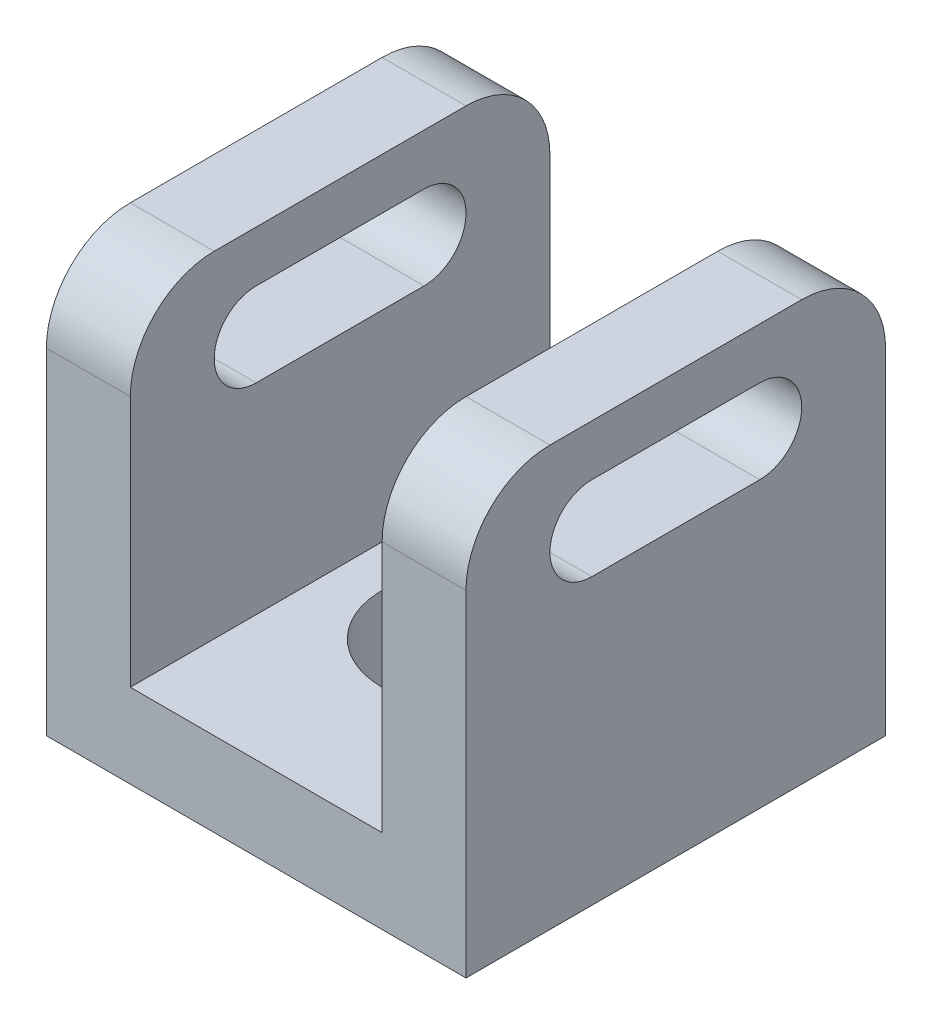
SolidWorks part; units mm, degrees
ref_plane "Ön Düzlem" through (0, 0, 0) normal (0, 0, 1) x (1, 0, 0)
ref_plane "Üst Düzlem" through (0, 0, 0) normal (0, 1, 0) x (1, 0, 0)
ref_plane "Sağ Düzlem" through (0, 0, 0) normal (1, 0, 0) x (0, 0, -1)
sketch "Çizim1" plane through (0, 0, 0) normal (0, 0, 1) x (1, 0, 0)
  line L1 (-57.2312, -11.2575) -> (-27.2312, -11.2575)
  line L2 (-67.2312, 21.7066) -> (-67.2312, -21.2575)
  line L3 (-67.2312, -21.2575) -> (-17.2312, -21.2575)
  line L4 (-17.2312, 21.7066) -> (-17.2312, -21.2575)
  line L6 (-67.2312, 21.7066) -> (-67.2312, 28.7425)
  line L7 (-67.2312, 28.7425) -> (-57.2312, 28.7425)
  line L8 (-57.2312, -11.2575) -> (-57.2312, 28.7425)
  line L10 (-17.2312, 21.7066) -> (-17.2312, 28.7425)
  line L11 (-17.2312, 28.7425) -> (-27.2312, 28.7425)
  line L12 (-27.2312, -11.2575) -> (-27.2312, 28.7425)
  dimension "D1" = 50
  dimension "D2" = 50
  dimension "D3" = 50
  dimension "D4" = 30
  dimension "D5" = 10
  dimension "D6" = 40
extrude "Yükseklik-Ekstrüzyon1" add sketch "Çizim1" along normal blind 50
sketch "Çizim2" plane through (0, -11.2575, 0) normal (0, 1, 0) x (1, 0, 0)
  circle A0 centre (-42.2312, -25) radius 10
  dimension "D1" = 20
extrude "Kes-Ekstrüzyon1" cut sketch "Çizim2" against normal up to next
sketch "Çizim3" plane through (-17.2312, 0, 0) normal (1, 0, 0) x (0, 0, -1)
  line L0 (-35, 17.6626) -> (-15, 17.6626) construction
  line L1 (-35, 22.6626) -> (-15, 22.6626)
  line L2 (-35, 12.6626) -> (-15, 12.6626)
  line L3 (-50, -21.2575) -> (-50, 28.7425) construction
  arc A0 (-35, 22.6626) -> (-35, 12.6626) centre (-35, 17.6626) ccw
  arc A1 (-15, 12.6626) -> (-15, 22.6626) centre (-15, 17.6626) ccw
  point P2 (-25, 17.6626)
  dimension "D3" = 5
  dimension "D1" = 20
  dimension "D2" = 15
extrude "Kes-Ekstrüzyon2" cut sketch "Çizim3" against normal through all both and the other way through all
fillet "Radyus1" radius 10 2 edges at (-62.2312, 28.7425, 50) (-62.2312, 28.7425, 0)
fillet "Radyus2" radius 10 2 edges at (-22.2312, 28.7425, 0) (-22.2312, 28.7425, 50)
